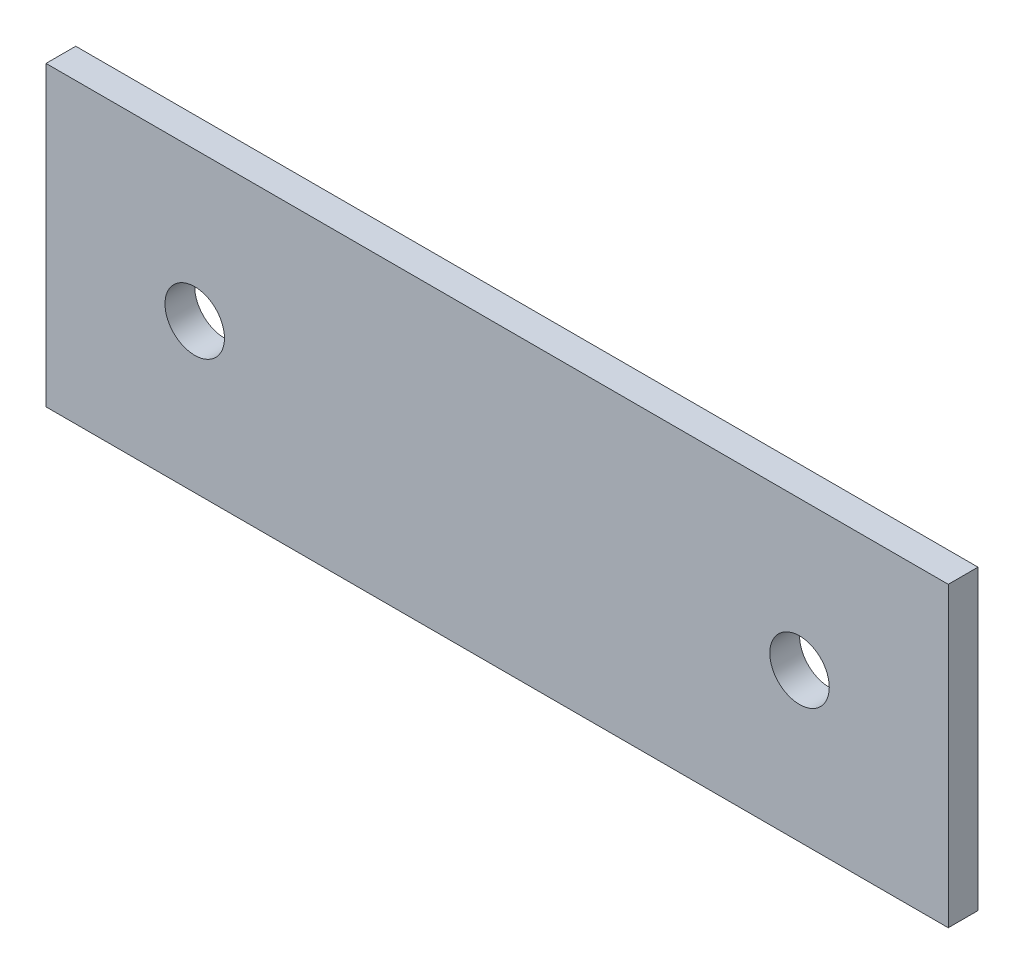
SolidWorks part; units mm, degrees
ref_plane "Plan de face" through (0, 0, 0) normal (0, 0, 1) x (1, 0, 0)
ref_plane "Plan de dessus" through (0, 0, 0) normal (0, 1, 0) x (1, 0, 0)
ref_plane "Plan de droite" through (0, 0, 0) normal (1, 0, 0) x (0, 0, -1)
sketch "Esquisse1" plane through (0, 0, 0) normal (0, 0, 1) x (1, 0, 0)
  line L0 (-36.0673, 7.4994) -> (9.4327, 7.4994) construction
  line L1 (-36.0673, 14.9994) -> (9.4327, 14.9994)
  line L2 (-36.0673, 14.9994) -> (-36.0673, -0.0006)
  line L3 (-36.0673, -0.0006) -> (9.4327, -0.0006)
  line L4 (9.4327, 14.9994) -> (9.4327, -0.0006)
  circle A0 centre (-28.5673, 7.4994) radius 1.5
  circle A1 centre (1.9327, 7.4994) radius 1.5
  dimension "D3" = 7.5
  dimension "D1" = 45.5
  dimension "D2" = 15
  dimension "D4" = 7.5
extrude "Extrusion1" add sketch "Esquisse1" along normal blind 1.5
